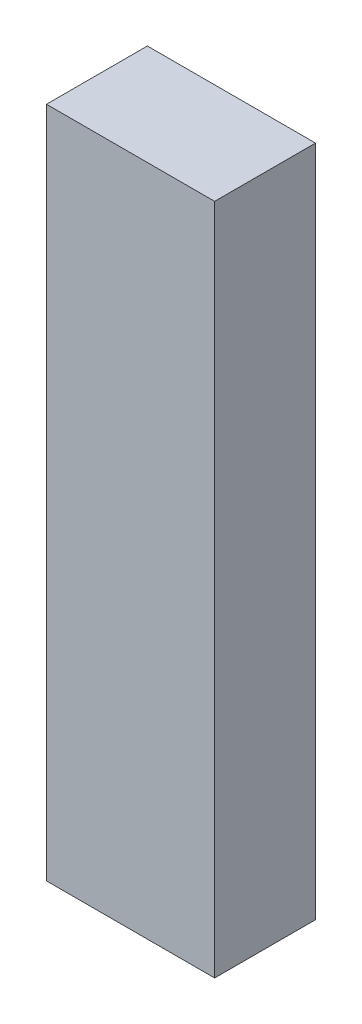
SolidWorks part; units mm, degrees
material "Cedro"
ref_plane "Alzado" through (0, 0, 0) normal (0, 0, 1) x (1, 0, 0)
ref_plane "Planta" through (0, 0, 0) normal (0, 1, 0) x (1, 0, 0)
ref_plane "Vista lateral" through (0, 0, 0) normal (1, 0, 0) x (0, 0, -1)
sketch "Croquis1" plane through (0, 0, 0) normal (0, 1, 0) x (1, 0, 0)
  line L1 (-12.5, -7.5) -> (12.5, -7.5)
  line L2 (-12.5, -7.5) -> (-12.5, 7.5)
  line L3 (-12.5, 7.5) -> (12.5, 7.5)
  line L4 (12.5, -7.5) -> (12.5, 7.5)
  line L5 (-12.5, -7.5) -> (12.5, 7.5) construction
  line L6 (-12.5, 7.5) -> (12.5, -7.5) construction
  point P0 (0, 0)
  dimension "D1" = 15
  dimension "D2" = 25
extrude "Saliente-Extruir1" add sketch "Croquis1" along normal blind 100
